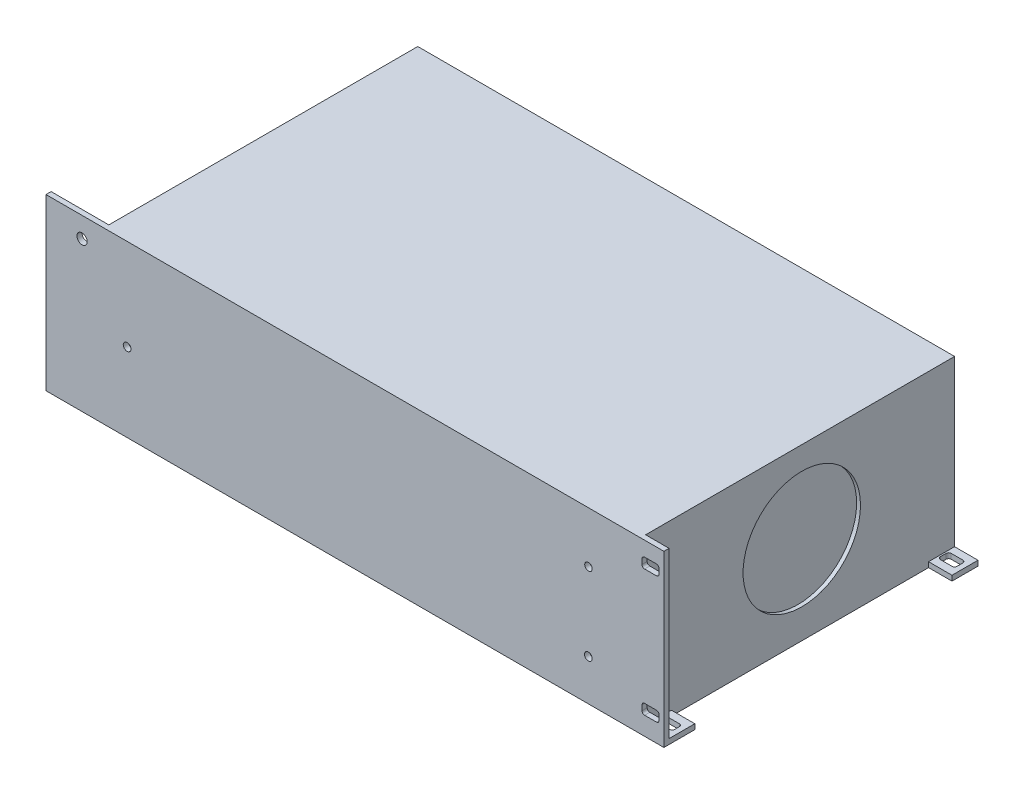
SolidWorks part; units mm, degrees
material "Stal węglowa"
ref_plane "Front" through (0, 0, 0) normal (0, 0, 1) x (1, 0, 0)
ref_plane "Top" through (0, 0, 0) normal (0, 1, 0) x (1, 0, 0)
ref_plane "Right" through (0, 0, 0) normal (1, 0, 0) x (0, 0, -1)
sketch "Szkic1" plane through (0, 0, 0) normal (0, 1, 0) x (1, 0, 0)
  line L1 (-90.566, 75.3962) -> (149.434, 75.3962)
  line L2 (-90.566, 75.3962) -> (-90.566, -46.6038)
  line L3 (-90.566, -46.6038) -> (149.434, -46.6038)
  line L4 (149.434, 75.3962) -> (149.434, -46.6038)
  dimension "D1" = 240
  dimension "D2" = 122
extrude "Dodanie-wyciągnięcie1" add sketch "Szkic1" along normal blind 2
sketch "Szkic2" plane through (0, 2, 0) normal (0, 1, 0) x (1, 0, 0)
  line L0 (149.434, -46.6038) -> (149.434, 75.3962) construction
  line L1 (-90.566, -46.6038) -> (149.434, -46.6038)
  line L2 (-90.566, -46.6038) -> (-90.566, -44.6038)
  line L3 (-90.566, -44.6038) -> (149.434, -44.6038)
  line L4 (149.434, -46.6038) -> (149.434, -44.6038)
  dimension "D1" = 2
extrude "Dodanie-wyciągnięcie2" add sketch "Szkic2" along normal blind 64
sketch "Szkic3" plane through (0, 2, 0) normal (0, 1, 0) x (1, 0, 0)
  line L0 (149.434, -34.6038) -> (-111.1402, -34.6038) construction
  line L1 (149.434, -44.6038) -> (149.434, 75.3962) construction
  line L2 (-90.566, -46.6038) -> (149.434, -46.6038) construction
  line L3 (149.434, 65.2962) -> (-106.9135, 65.2962) construction
  line L4 (149.434, 75.3962) -> (-90.566, 75.3962) construction
  line L5 (140.334, -34.6038) -> (140.334, 65.2962) construction
  line L6 (-85.066, -34.6038) -> (-85.066, 99.7277) construction
  line L7 (140.334, -34.6038) -> (149.434, -34.6038)
  line L8 (140.334, -34.6038) -> (140.334, 65.2962)
  line L9 (140.334, 65.2962) -> (149.434, 65.2962)
  line L10 (149.434, -34.6038) -> (149.434, 65.2962)
  line L11 (-90.566, 75.3962) -> (-90.566, -44.6038) construction
  line L13 (-85.066, -34.6038) -> (-90.566, -34.6038)
  line L14 (-85.066, -34.6038) -> (-85.066, 65.2962)
  line L15 (-85.066, 65.2962) -> (-90.566, 65.2962)
  line L16 (-90.566, -34.6038) -> (-90.566, 65.2962)
  dimension "D1" = 12
  dimension "D2" = 10.1
  dimension "D3" = 9.1
  dimension "D4" = 5.5
extrude "Wytnij-wyciągnięcie1" cut sketch "Szkic3" against normal through all
sketch "Szkic4" plane through (0, 2, 0) normal (0, 1, 0) x (1, 0, 0)
  line L0 (140.334, 65.2962) -> (140.334, 102.533) construction
  line L1 (140.334, 75.3962) -> (-68.166, 75.3962)
  line L2 (149.434, 75.3962) -> (-90.566, 75.3962) construction
  line L3 (-68.166, 75.3962) -> (-68.166, -44.6038)
  line L4 (149.434, -44.6038) -> (-90.566, -44.6038) construction
  line L5 (-68.166, -44.6038) -> (140.334, -44.6038)
  line L6 (140.334, -44.6038) -> (140.334, 75.3962)
  dimension "D1" = 208.5
extrude "Dodanie-wyciągnięcie3" add sketch "Szkic4" along normal blind 64
sketch "Szkic5" plane through (140.334, 0, 0) normal (1, 0, 0) x (0, 0, -1)
  circle A0 centre (16.0479, 34.2394) radius 22.8063
extrude "Wytnij-wyciągnięcie2" cut sketch "Szkic5" against normal blind 1.5
sketch "Szkic6" plane through (0, 2, 0) normal (0, 1, 0) x (1, 0, 0)
  line L0 (-85.066, -34.6038) -> (-85.066, 65.2962) construction
  line L1 (-85.066, -29.9406) -> (-68.166, -29.9406)
  line L2 (-85.066, -29.9406) -> (-85.066, 60.4089)
  line L3 (-85.066, 60.4089) -> (-68.166, 60.4089)
  line L4 (-68.166, -29.9406) -> (-68.166, 60.4089)
  line L5 (-68.166, 75.3962) -> (-68.166, -44.6038) construction
extrude "Dodanie-wyciągnięcie4" add sketch "Szkic6" along normal blind 20
sketch "Szkic7" plane through (0, 2, 0) normal (0, 1, 0) x (1, 0, 0)
  line L0 (140.334, 72.4962) -> (160.1391, 72.4962) construction
  line L1 (140.334, 65.2962) -> (140.334, 75.3962) construction
  line L2 (149.434, 75.3962) -> (140.334, 75.3962) construction
  line L3 (140.334, 68.2962) -> (165.9786, 68.2962) construction
  line L4 (149.434, 65.2962) -> (140.334, 65.2962) construction
  line L5 (147.434, -41.4038) -> (147.434, 86.0555) construction
  line L6 (149.434, 65.2962) -> (149.434, 75.3962) construction
  line L7 (140.934, -41.4038) -> (140.934, 80.0004) construction
  line L8 (140.334, -41.4038) -> (154.5338, -41.4038) construction
  line L9 (141.9134, 72.4962) -> (146.4545, 72.4962)
  line L10 (140.934, 71.5168) -> (140.934, 69.2757)
  line L11 (141.9134, 68.2962) -> (146.4545, 68.2962)
  line L12 (147.434, 71.5168) -> (147.434, 69.2757)
  line L13 (140.334, -44.6038) -> (140.334, -34.6038) construction
  line L14 (-90.566, -46.6038) -> (149.434, -46.6038) construction
  line L15 (140.334, -37.6038) -> (158.3104, -37.6038) construction
  line L16 (140.334, -34.6038) -> (149.434, -34.6038) construction
  line L18 (141.9134, -37.6038) -> (146.4545, -37.6038)
  line L19 (140.934, -38.5832) -> (140.934, -40.4243)
  line L20 (141.9134, -41.4038) -> (146.4545, -41.4038)
  line L21 (147.434, -38.5832) -> (147.434, -40.4243)
  arc A0 (141.9134, 72.4962) -> (140.934, 71.5168) centre (141.9134, 71.5168) ccw
  arc A1 (140.934, 69.2757) -> (141.9134, 68.2962) centre (141.9134, 69.2757) ccw
  arc A2 (146.4545, 68.2962) -> (147.434, 69.2757) centre (146.4545, 69.2757) ccw
  arc A3 (147.434, 71.5168) -> (146.4545, 72.4962) centre (146.4545, 71.5168) ccw
  arc A4 (141.9134, -37.6038) -> (140.934, -38.5832) centre (141.9134, -38.5832) ccw
  arc A5 (140.934, -40.4243) -> (141.9134, -41.4038) centre (141.9134, -40.4243) ccw
  arc A6 (146.4545, -41.4038) -> (147.434, -40.4243) centre (146.4545, -40.4243) ccw
  arc A7 (147.434, -38.5832) -> (146.4545, -37.6038) centre (146.4545, -38.5832) ccw
  point P22 (140.934, 72.4962)
  point P27 (147.434, 68.2962)
  point P44 (140.934, -37.6038)
  dimension "D5" = 0.9794
  dimension "D8" = 0.9794
  dimension "D1" = 2.9
  dimension "D2" = 3
  dimension "D3" = 2
  dimension "D4" = 6.5
  dimension "D6" = 5.2
  dimension "D7" = 3
extrude "Wytnij-wyciągnięcie3" cut sketch "Szkic7" against normal through all
sketch "Szkic8" plane through (0, 2, 0) normal (0, 1, 0) x (1, 0, 0)
  line L0 (-88.566, -41.3538) -> (-88.566, 89.7984) construction
  line L2 (-90.566, 75.3962) -> (-90.566, 65.2962) construction
  line L3 (-84.566, -41.3538) -> (-84.566, 94.3247) construction
  line L4 (-71.529, 72.5962) -> (-97.4433, 72.5962) construction
  line L5 (-68.166, 75.3962) -> (-90.566, 75.3962) construction
  line L6 (-71.529, 68.5962) -> (-111.4398, 68.5962) construction
  line L7 (-88.566, 72.5962) -> (-84.566, 68.5962) construction
  line L8 (-68.166, -41.3538) -> (-117.2524, -41.3538) construction
  line L9 (-68.166, -29.9406) -> (-68.166, -44.6038) construction
  line L10 (-90.566, -46.6038) -> (149.434, -46.6038) construction
  line L11 (-74.628, -37.3538) -> (-119.1855, -37.3538) construction
  line L12 (-88.566, -37.3538) -> (-84.566, -41.3538) construction
  circle A0 centre (-86.566, 70.5962) radius 2
  circle A1 centre (-86.566, -39.3538) radius 2
  dimension "D1" = 2
  dimension "D2" = 4
  dimension "D3" = 2.8
  dimension "D4" = 4
  dimension "D5" = 5.25
  dimension "D6" = 4
extrude "Wytnij-wyciągnięcie4" cut sketch "Szkic8" against normal through all
sketch "Szkic9" plane through (0, 0, 0) normal (0, -1, 0) x (1, 0, 0)
  line L0 (127.4439, 38.8038) -> (-165.8114, 38.8038) construction
  line L1 (-90.566, 46.6038) -> (149.434, 46.6038) construction
  line L2 (106.734, 161.4279) -> (106.734, -72.5962) construction
  line L3 (109.934, 108.1602) -> (109.934, -72.5962) construction
  line L4 (149.434, 46.6038) -> (149.434, 34.6038) construction
  line L5 (-78.566, -72.5962) -> (-78.566, 87.5476) construction
  line L6 (-90.566, 34.6038) -> (-90.566, 46.6038) construction
  line L7 (-75.366, -72.5962) -> (-75.366, 103.3813) construction
  line L8 (-78.566, 35.6038) -> (118.8726, 35.6038) construction
  line L9 (-68.9692, -69.3962) -> (254.4433, -69.3962) construction
  line L10 (-68.9692, -69.3962) -> (-130.0568, -69.3962) construction
  line L11 (-116.2109, -72.5962) -> (158.9069, -72.5962) construction
  line L12 (-78.566, 38.8038) -> (-75.366, 35.6038) construction
  line L13 (106.734, 38.8038) -> (109.934, 35.6038) construction
  line L14 (106.734, -69.3962) -> (109.934, -72.5962) construction
  line L15 (-78.566, -69.3962) -> (-75.2638, -72.6985) construction
  circle A0 centre (-76.966, 37.2038) radius 1.6
  circle A1 centre (108.334, 37.2038) radius 1.6
  circle A2 centre (108.334, -70.9962) radius 1.6
  circle A3 centre (-76.9149, -71.0473) radius 1.6511
  dimension "D1" = 7.8
  dimension "D2" = 39.5
  dimension "D3" = 3.2
  dimension "D4" = 12
  dimension "D5" = 3.2
  dimension "D6" = 3.2
  dimension "D7" = 105
  dimension "D8" = 3.2
extrude "Wytnij-wyciągnięcie5" cut sketch "Szkic9" against normal blind 2
sketch "Szkic10" plane through (0, 0, 46.6038) normal (0, 0, 1) x (1, 0, 0)
  line L0 (147.534, 7.1) -> (147.534, 60.3295) construction
  line L1 (149.434, 66) -> (149.434, 0) construction
  line L2 (140.934, 0) -> (140.934, 110.0898) construction
  line L3 (-90.566, 0) -> (149.434, 0) construction
  line L4 (113.5567, 60.3) -> (177.7826, 60.3) construction
  line L5 (-90.566, 66) -> (149.434, 66) construction
  line L6 (120.2139, 56.3) -> (189.3536, 56.3) construction
  line L7 (113.5567, 11.1) -> (203.2469, 11.1) construction
  line L8 (114.5703, 7.1) -> (217.3294, 7.1) construction
  line L9 (-78.566, 42.8657) -> (-78.566, 94.5074) construction
  line L10 (141.934, 60.3) -> (146.534, 60.3)
  line L11 (140.934, 59.3) -> (140.934, 57.3)
  line L12 (141.934, 56.3) -> (146.534, 56.3)
  line L13 (147.534, 59.3) -> (147.534, 57.3)
  line L14 (141.934, 11.1) -> (146.534, 11.1)
  line L15 (140.934, 10.1) -> (140.934, 8.1)
  line L16 (141.934, 7.1) -> (146.534, 7.1)
  line L17 (147.534, 10.1) -> (147.534, 8.1)
  line L18 (-90.566, 66) -> (-90.566, 0) construction
  line L19 (-47.9493, 60.1) -> (-160.6721, 60.1) construction
  line L20 (-78.566, 56.1) -> (-54.5895, 56.1) construction
  line L21 (-74.566, 66) -> (-74.566, 47.3869) construction
  line L22 (-78.566, 60.1) -> (-74.566, 56.1) construction
  arc A0 (141.934, 11.1) -> (140.934, 10.1) centre (141.934, 10.1) ccw
  arc A1 (140.934, 8.1) -> (141.934, 7.1) centre (141.934, 8.1) ccw
  arc A2 (146.534, 7.1) -> (147.534, 8.1) centre (146.534, 8.1) ccw
  arc A3 (147.534, 10.1) -> (146.534, 11.1) centre (146.534, 10.1) ccw
  arc A4 (141.934, 60.3) -> (140.934, 59.3) centre (141.934, 59.3) ccw
  arc A5 (140.934, 57.3) -> (141.934, 56.3) centre (141.934, 57.3) ccw
  arc A6 (147.534, 57.3) -> (146.534, 56.3) centre (146.534, 57.3) cw
  arc A7 (146.534, 60.3) -> (147.534, 59.3) centre (146.534, 59.3) cw
  circle A8 centre (-76.566, 58.1) radius 2
  point P27 (140.934, 11.1)
  point P37 (140.934, 60.3)
  point P42 (147.534, 56.3)
  dimension "D7" = 1
  dimension "D1" = 1.9
  dimension "D2" = 6.6
  dimension "D3" = 5.7
  dimension "D4" = 4
  dimension "D5" = 45.2
  dimension "D6" = 4
  dimension "D8" = 12
  dimension "D9" = 5.9
  dimension "D10" = 4
  dimension "D11" = 4
extrude "Wytnij-wyciągnięcie6" cut sketch "Szkic10" against normal blind 2
sketch "Szkic11" plane through (0, 0, 46.6038) normal (0, 0, 1) x (1, 0, 0)
  line L0 (121.634, 91.7298) -> (121.634, -11.6554) construction
  line L1 (149.434, 66) -> (149.434, 0) construction
  line L2 (118.634, 107.0249) -> (118.634, -8.9016) construction
  line L3 (41.7964, 47.6) -> (173.2083, 47.6) construction
  line L4 (-90.566, 66) -> (149.434, 66) construction
  line L5 (38.2818, 14.45) -> (199.3009, 14.45) construction
  line L6 (130.7548, 44.6) -> (106.1909, 44.6) construction
  line L7 (109.4226, 17.45) -> (127.662, 17.45) construction
  line L8 (118.5423, 17.45) -> (121.634, 14.45) construction
  line L9 (118.634, 47.6) -> (121.634, 44.6889) construction
  line L10 (-60.566, 98.5574) -> (-60.566, -44.162) construction
  line L11 (-90.566, 66) -> (-90.566, 0) construction
  line L12 (-46.4752, 32) -> (-122.5585, 32) construction
  line L13 (-57.566, 40.6658) -> (-57.566, 21.5991) construction
  line L14 (-48.2889, 29) -> (-75.815, 29) construction
  line L15 (-60.566, 32) -> (-57.566, 29) construction
  circle A0 centre (120.134, 46.1445) radius 1.4555
  circle A1 centre (120.0881, 15.95) radius 1.5
  circle A2 centre (-59.066, 30.5) radius 1.5
  dimension "D1" = 27.8
  dimension "D2" = 3
  dimension "D3" = 18.4
  dimension "D4" = 33.15
  dimension "D5" = 3
  dimension "D6" = 3
  dimension "D7" = 30
  dimension "D8" = 34
  dimension "D9" = 3
  dimension "D10" = 3
extrude "Wytnij-wyciągnięcie7" cut sketch "Szkic11" against normal blind 2
